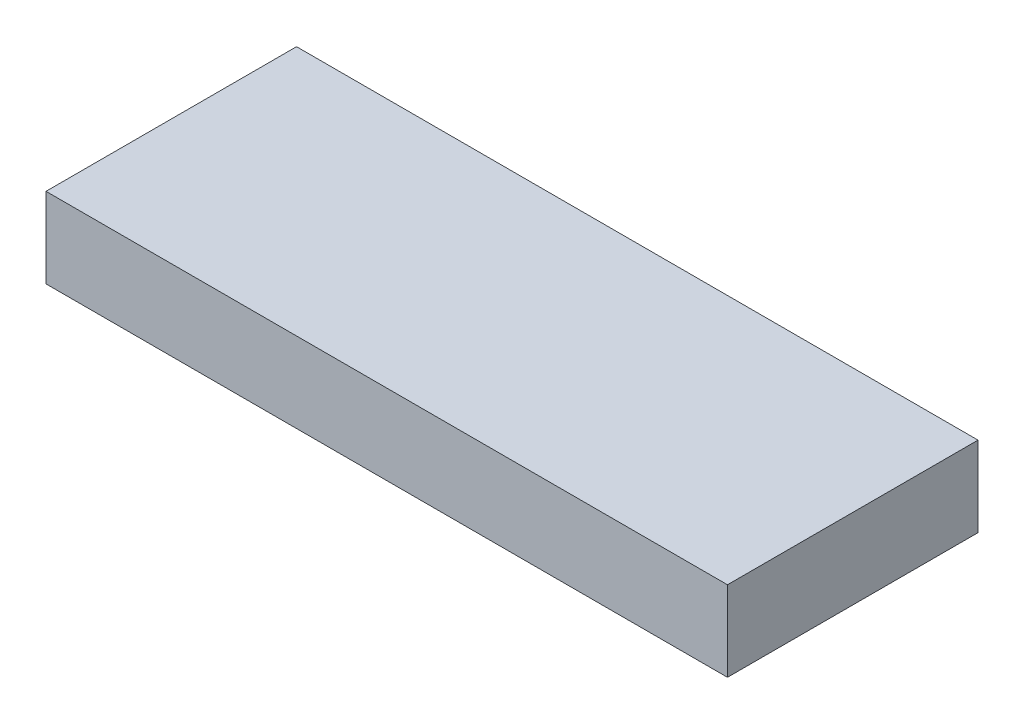
SolidWorks part; units mm, degrees
ref_plane "Front Plane" through (0, 0, 0) normal (0, 0, 1) x (1, 0, 0)
ref_plane "Top Plane" through (0, 0, 0) normal (0, 1, 0) x (1, 0, 0)
ref_plane "Right Plane" through (0, 0, 0) normal (1, 0, 0) x (0, 0, -1)
sketch "Sketch1" plane through (0, 0, 0) normal (0, 1, 0) x (1, 0, 0)
  line L1 (0, 0) -> (-68, 0)
  line L2 (0, 0) -> (0, 25)
  line L3 (0, 25) -> (-68, 25)
  line L4 (-68, 0) -> (-68, 25)
  dimension "D1" = 68
  dimension "D2" = 25
extrude "Boss-Extrude1" add sketch "Sketch1" along normal blind 8
